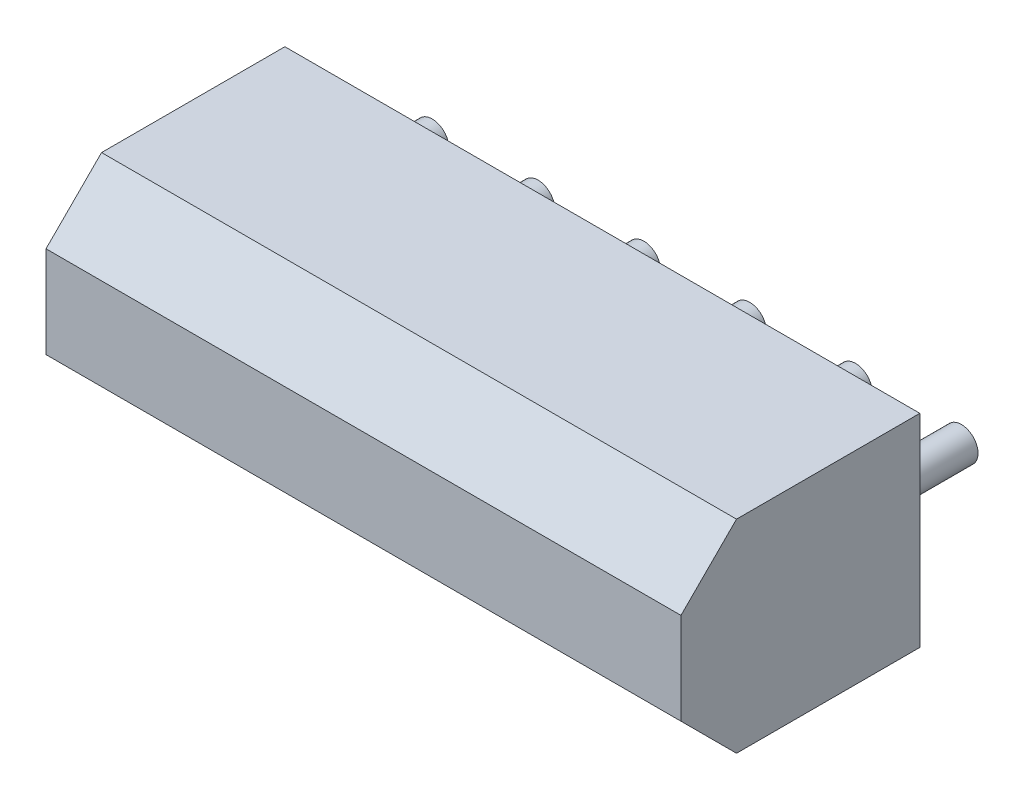
SolidWorks part; units mm, degrees
ref_plane "前视基准面" through (0, 0, 0) normal (0, 0, 1) x (1, 0, 0)
ref_plane "上视基准面" through (0, 0, 0) normal (0, 1, 0) x (1, 0, 0)
ref_plane "右视基准面" through (0, 0, 0) normal (1, 0, 0) x (0, 0, -1)
sketch "草图1" plane through (0, 0, 0) normal (0, 0, 1) x (1, 0, 0)
  line L1 (0, 0) -> (22.86, 0)
  line L2 (0, 0) -> (0, 7.3)
  line L3 (0, 7.3) -> (22.86, 7.3)
  line L4 (22.86, 0) -> (22.86, 7.3)
  dimension "D1" = 22.86
  dimension "D2" = 7.3
extrude "凸台-拉伸1" add sketch "草图1" along normal blind 8.6
chamfer "倒角1" distance 2 angle 45 2 edges at (11.43, 0, 8.6) (11.43, 7.3, 8.6)
sketch "草图2" plane through (0, 0, 0) normal (0, -1, 0) x (1, 0, 0)
  line L1 (12.585, 4.7244) -> (14.085, 4.7244)
  line L2 (12.585, 4.7244) -> (12.585, 2.4797)
  line L3 (12.585, 2.4797) -> (14.085, 2.4797)
  line L4 (14.085, 4.7244) -> (14.085, 2.4797)
  line L5 (11.43, 0) -> (11.43, 12.0535) construction
  line L6 (0, 0) -> (22.86, 0) construction
  line L7 (13.335, 4.7244) -> (13.335, 1.5061) construction
  dimension "D1" = 1.905
  dimension "D2" = 1.5
extrude "切除-拉伸1" cut sketch "草图2" against normal blind 0.5
pattern_linear "阵列(线性)1" count 3 spacing 3.81 along (1, 0, 0) count 4 spacing 3.81 along (-1, 0, 0) of "切除-拉伸1"
sketch "草图3" plane through (0, 0, 0) normal (0, 0, -1) x (-1, 0, 0)
  line L0 (-22.86, 3.7) -> (2.0184, 3.7) construction
  line L1 (-22.86, 0) -> (-22.86, 7.3) construction
  line L2 (-22.86, 7.3) -> (0, 7.3) construction
  line L3 (-11.43, 7.3) -> (-11.43, -1.5587) construction
  circle A0 centre (-13.335, 3.7) radius 0.6
  dimension "D2" = 1.2
  dimension "D1" = 3.6
  dimension "D3" = 1.905
extrude "凸台-拉伸2" add sketch "草图3" along normal blind 3.4
pattern_linear "阵列(线性)2" count 4 spacing 3.81 along (-1, 0, 0) count 3 spacing 3.81 along (1, 0, 0) of "凸台-拉伸2"
pattern_linear "阵列(线性)3" count 2 spacing 3.81 along (-1, 0, 0) of "凸台-拉伸2"
